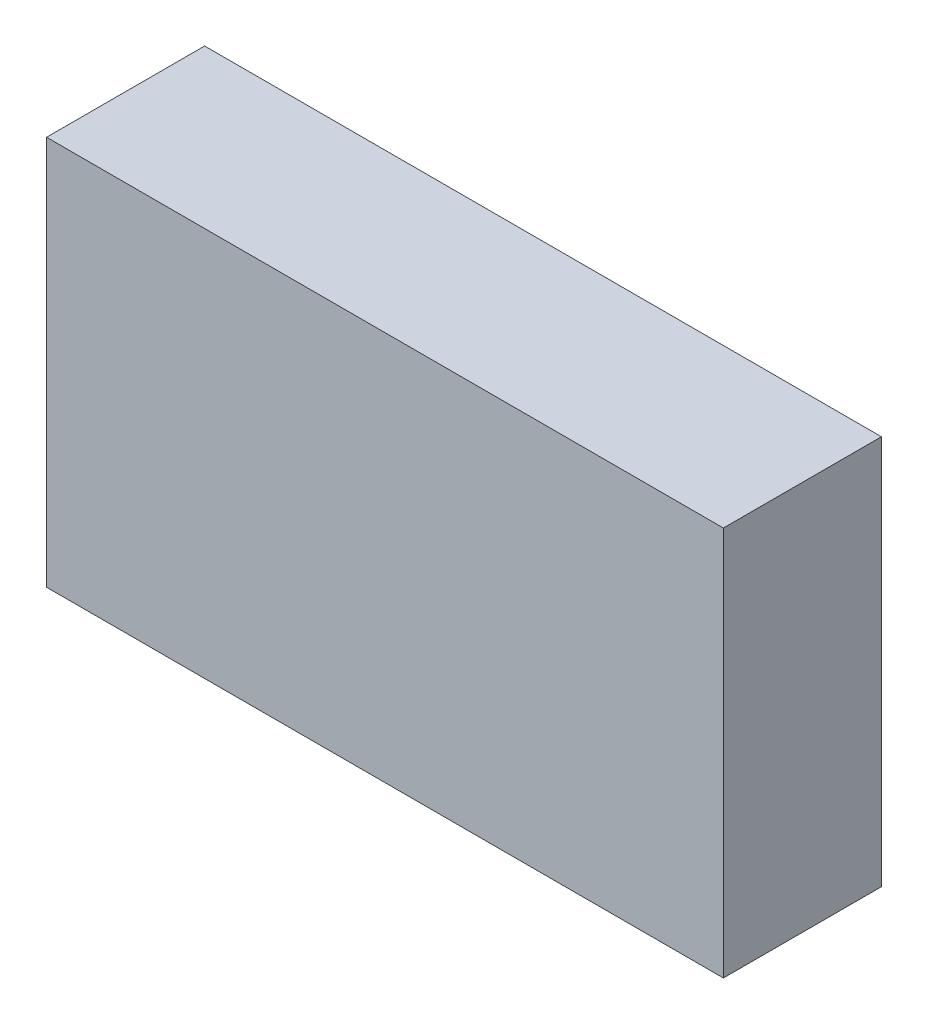
SolidWorks part; units mm, degrees
ref_plane "Front Plane" through (0, 0, 0) normal (0, 0, 1) x (1, 0, 0)
ref_plane "Top Plane" through (0, 0, 0) normal (0, 1, 0) x (1, 0, 0)
ref_plane "Right Plane" through (0, 0, 0) normal (1, 0, 0) x (0, 0, -1)
sketch "AnchorSketch" plane through (0, 0, 0) normal (0, 0, 1) x (1, 0, 0)
  line L1 (0, 0) -> (31.73, 0)
  line L2 (0, 0) -> (0, 18.27)
  line L3 (0, 18.27) -> (31.73, 18.27)
  line L4 (31.73, 0) -> (31.73, 18.27)
  dimension "D1" = 31.73
  dimension "D2" = 18.27
extrude "AnchorBoss" add sketch "AnchorSketch" along normal blind 7.41
